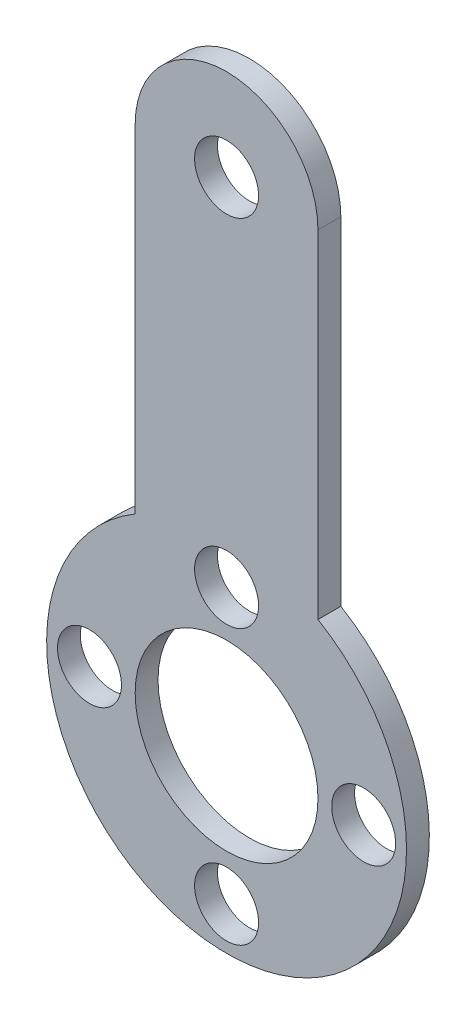
SolidWorks part; units mm, degrees
ref_plane "Front Plane" through (0, 0, 0) normal (0, 0, 1) x (1, 0, 0)
ref_plane "Top Plane" through (0, 0, 0) normal (0, 1, 0) x (1, 0, 0)
ref_plane "Right Plane" through (0, 0, 0) normal (1, 0, 0) x (0, 0, -1)
sketch "Sketch1" plane through (0, 0, 0) normal (0, 0, 1) x (1, 0, 0)
  line L0 (5.3436, -2.6082) -> (5.3436, 16.1418)
  line L2 (-4.8164, -2.6082) -> (-4.8164, 16.1418)
  circle A11 centre (0.2636, -11.2218) radius 7.62 construction
  circle A12 centre (0.2636, -3.6018) radius 1.778
  circle A15 centre (-7.3564, -11.2218) radius 1.778
  circle A16 centre (7.8836, -11.2218) radius 1.778
  circle A17 centre (0.2636, -18.8418) radius 1.778
  arc A18 (-4.8164, -2.6082) -> (5.3436, -2.6082) centre (0.2636, -11.2218) ccw
  circle A19 centre (0.2636, -11.2218) radius 5.08
  arc A20 (5.3436, 16.1418) -> (-4.8164, 16.1418) centre (0.2636, 16.1418) ccw
  circle A21 centre (0.2636, 16.1418) radius 1.778
  dimension "D8" = 3.556
  dimension "D17" = 3.556
  dimension "D18" = 3.556
  dimension "D19" = 3.556
  dimension "D20" = 10.16
  dimension "D21" = 3.556
extrude "Boss-Extrude1" add sketch "Sketch1" along normal blind 1.27
